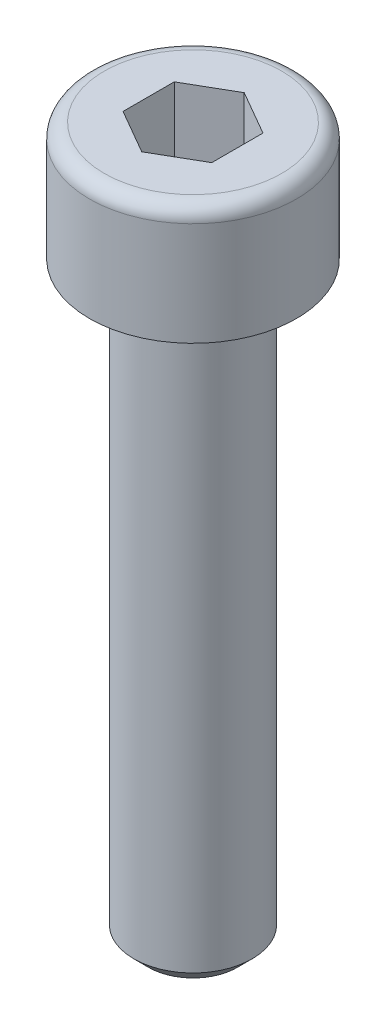
SolidWorks part; units mm, degrees
material "acero"
ref_plane "Alzado" through (0, 0, 0) normal (0, 0, 1) x (1, 0, 0)
ref_plane "Planta" through (0, 0, 0) normal (0, 1, 0) x (1, 0, 0)
ref_plane "Vista lateral" through (0, 0, 0) normal (1, 0, 0) x (0, 0, -1)
sketch "Croquis1" plane through (0, 0, 0) normal (0, 0, 1) x (1, 0, 0)
  line L0 (0, 0) -> (0, -60.9498) construction
  line L1 (0, 0) -> (3.5, 0)
  line L2 (3.5, 0) -> (3.5, -4)
  line L3 (3.5, -4) -> (2, -4)
  line L4 (2, -4) -> (2, -24)
  line L5 (2, -24) -> (0, -24)
  line L6 (0, -24) -> (0, 0)
  dimension "D1" = 20
  dimension "D2" = 4
  dimension "D3" = 7
  dimension "D4" = 4
revolve "Revolución1" add sketch "Croquis1" angle 360 about L0
sketch "Croquis2" plane through (0, 0, 0) normal (0, 1, 0) x (1, 0, 0)
  line L1 (1.5, 0.866) -> (0, 1.7321)
  line L2 (0, 1.7321) -> (-1.5, 0.866)
  line L3 (-1.5, 0.866) -> (-1.5, -0.866)
  line L4 (-1.5, -0.866) -> (0, -1.7321)
  line L5 (0, -1.7321) -> (1.5, -0.866)
  line L6 (1.5, -0.866) -> (1.5, 0.866)
  circle A0 centre (0, 0) radius 1.5 construction
  dimension "D1" = 3
extrude "Cortar-Extruir1" cut sketch "Croquis2" against normal blind 3
chamfer "Chaflán1" distance 0.5 angle 45 1 edges at (0, -24, 2)
fillet "Redondeo1" radius 0.5 1 edges at (0, 0, 3.5)
